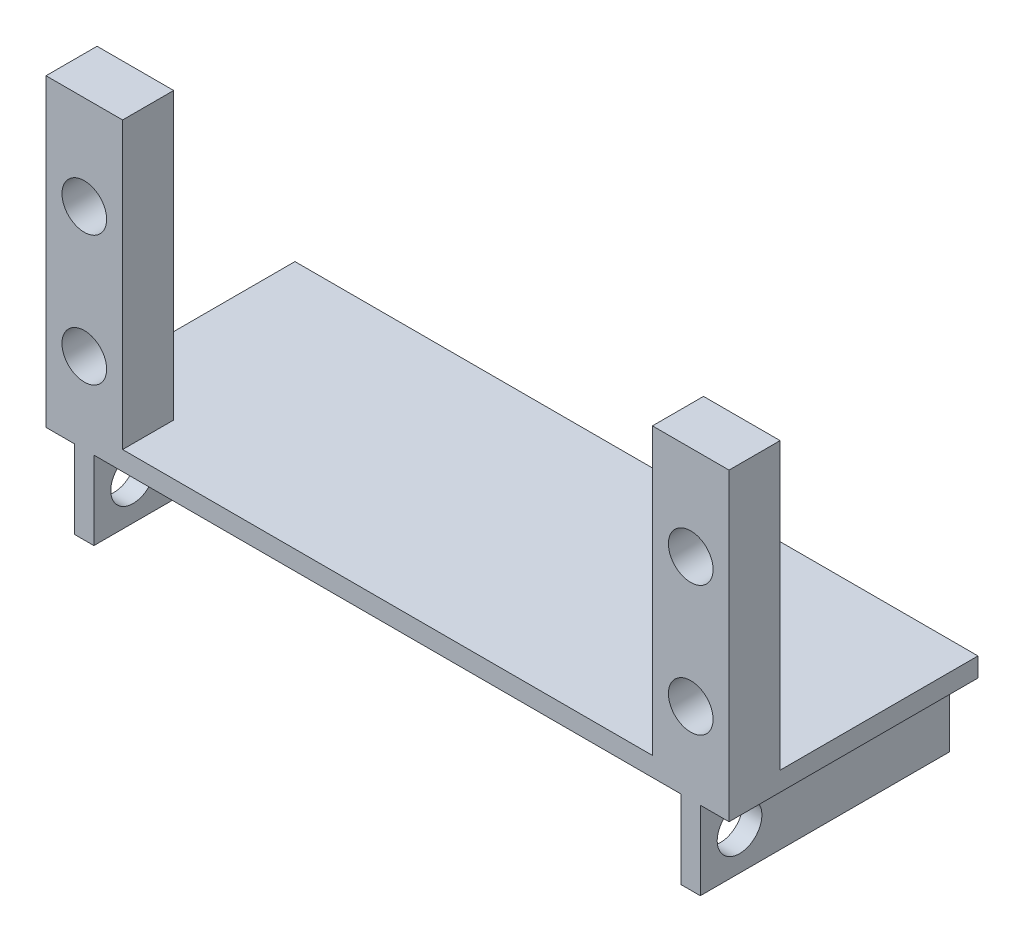
SolidWorks part; units mm, degrees
ref_plane "Front" through (0, 0, 0) normal (0, 0, 1) x (1, 0, 0)
ref_plane "Top" through (0, 0, 0) normal (0, 1, 0) x (1, 0, 0)
ref_plane "Right" through (0, 0, 0) normal (1, 0, 0) x (0, 0, -1)
sketch "Esquisse1" plane through (0, 0, 0) normal (0, 1, 0) x (1, 0, 0)
  line L1 (-26.75, 9.75) -> (26.75, 9.75)
  line L2 (-26.75, 9.75) -> (-26.75, -9.75)
  line L3 (-26.75, -9.75) -> (26.75, -9.75)
  line L4 (26.75, 9.75) -> (26.75, -9.75)
  line L5 (-26.75, 9.75) -> (26.75, -9.75) construction
  line L6 (-26.75, -9.75) -> (26.75, 9.75) construction
  point P0 (0, 0)
  dimension "D1" = 19.5
  dimension "D2" = 53.5
extrude "Boss.-Extru.1" add sketch "Esquisse1" along normal blind 1.5
sketch "Esquisse2" plane through (0, 1.5, 0) normal (0, 1, 0) x (1, 0, 0)
  line L0 (-26.75, -9.75) -> (26.75, -9.75) construction
  line L1 (-26.75, -9.75) -> (-20.75, -9.75)
  line L2 (-26.75, -9.75) -> (-26.75, -5.75)
  line L3 (-26.75, -5.75) -> (-20.75, -5.75)
  line L4 (-20.75, -9.75) -> (-20.75, -5.75)
  line L6 (26.75, -9.75) -> (20.75, -9.75)
  line L7 (26.75, -9.75) -> (26.75, -5.75)
  line L8 (26.75, -5.75) -> (20.75, -5.75)
  line L9 (20.75, -9.75) -> (20.75, -5.75)
  point P10 (-23.75, -5.75)
  point P11 (23.75, -5.75)
  point P12 (0, -9.75)
  dimension "D1" = 4
  dimension "D2" = 4
  dimension "D3" = 6
  dimension "D4" = 6
  dimension "D5" = 47.5
  dimension "D6" = 23.75
extrude "Boss.-Extru.2" add sketch "Esquisse2" along normal blind 22.356
sketch "Esquisse3" plane through (0, 0, 0) normal (0, -1, 0) x (1, 0, 0)
  line L0 (-26.75, 9.75) -> (26.75, 9.75) construction
  line L1 (-24.5, 9.75) -> (-23, 9.75)
  line L2 (-24.5, 9.75) -> (-24.5, -9.75)
  line L3 (-24.5, -9.75) -> (-23, -9.75)
  line L4 (-23, 9.75) -> (-23, -9.75)
  line L5 (26.75, -9.75) -> (-26.75, -9.75) construction
  line L6 (-26.75, -9.75) -> (-26.75, 9.75) construction
  point P8 (-23.75, 9.75)
  dimension "D1" = 1.5
  dimension "D2" = 3
extrude "Boss.-Extru.3" add sketch "Esquisse3" along normal blind 6.144
mirror "Symétrie1" about plane through (0, 0, 0) normal (1, 0, 0) of "Boss.-Extru.3"
sketch "Esquisse4" plane through (0, 0, 0) normal (0, -1, 0) x (-1, 0, 0)
  line L0 (23, 9.75) -> (23, -9.75) construction
  line L1 (-23, 9.75) -> (23, 9.75)
  line L2 (-23, 9.75) -> (-23, 8.25)
  line L3 (-23, 8.25) -> (23, 8.25)
  line L4 (23, 9.75) -> (23, 8.25)
  dimension "D1" = 1.5
extrude "Boss.-Extru.4" add sketch "Esquisse4" along normal blind 6.144
sketch "Esquisse5" plane through (0, 0, 9.75) normal (0, 0, 1) x (1, 0, 0)
  line L0 (-26.75, 23.856) -> (-26.75, 0) construction
  line L1 (-23, -6.144) -> (-24.5, -6.144) construction
  circle A0 centre (-23.75, 6.326) radius 1.75
  circle A1 centre (-23.75, 16.486) radius 1.75
  point P8 (-23.75, -6.144)
  dimension "D1" = 3.5
  dimension "D2" = 3.5
  dimension "D3" = 3
  dimension "D4" = 3
  dimension "D5" = 12.47
  dimension "D6" = 22.63
extrude "Enlèv. mat.-Extru.1" cut sketch "Esquisse5" against normal up to next
mirror "Symétrie2" about plane through (0, 0, 0) normal (1, 0, 0) of "Enlèv. mat.-Extru.1"
sketch "Esquisse6" plane through (-24.5, 0, 0) normal (-1, 0, 0) x (0, 0, 1)
  line L0 (9.75, -6.144) -> (-9.75, -6.144) construction
  line L1 (9.75, -6.144) -> (9.75, 0) construction
  circle A0 centre (6.678, -3.072) radius 1.75
  dimension "D1" = 3.5
  dimension "D2" = 3.072
  dimension "D3" = 3.072
extrude "Enlèv. mat.-Extru.2" cut sketch "Esquisse6" against normal through all
